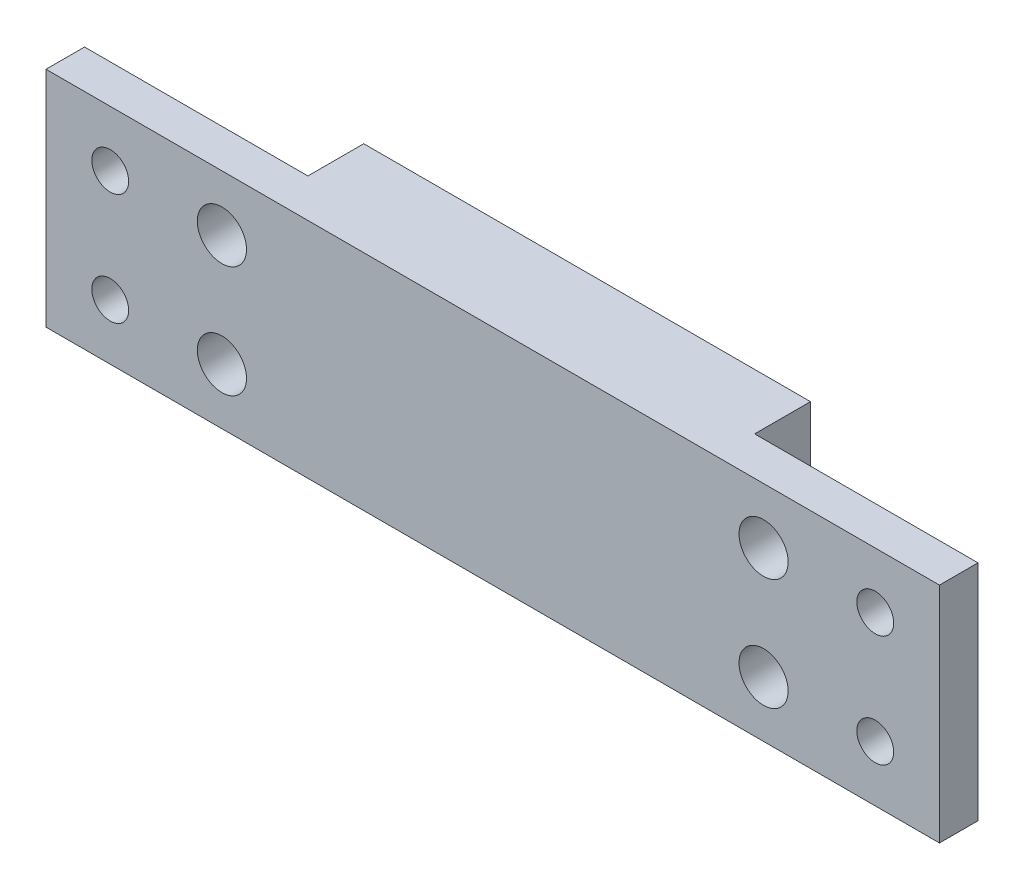
SolidWorks part; units mm, degrees
ref_plane "前视基准面" through (0, 0, 0) normal (0, 0, 1) x (1, 0, 0)
ref_plane "上视基准面" through (0, 0, 0) normal (0, 1, 0) x (1, 0, 0)
ref_plane "右视基准面" through (0, 0, 0) normal (1, 0, 0) x (0, 0, -1)
other "Configuration Table"
sketch "草图1" plane through (0, 0, 0) normal (0, 0, 1) x (1, 0, 0)
  line L1 (0, 0) -> (60, 0)
  line L2 (0, 0) -> (0, 20)
  line L3 (0, 20) -> (60, 20)
  line L4 (60, 0) -> (60, 20)
  dimension "D1" = 60
  dimension "D2" = 20
extrude "凸台-拉伸1" add sketch "草图1" along normal blind 3.45
sketch "草图2" plane through (0, 0, 0) normal (0, 0, -1) x (-1, 0, 0)
  line L0 (0, 0) -> (-60, 0) construction
  line L1 (-50, 0) -> (-10, 0)
  line L2 (-50, 0) -> (-50, 20)
  line L3 (-50, 20) -> (-10, 20)
  line L4 (-10, 0) -> (-10, 20)
  line L5 (-60, 20) -> (0, 20) construction
  line L6 (-30, 20) -> (-30, -10.5906) construction
  point P10 (-30, 20)
  point P11 (-30, 20)
  dimension "D1" = 40
extrude "凸台-拉伸2" add sketch "草图2" along normal blind 5
sketch "草图4" plane through (0, 0, 0) normal (0, 0, -1) x (-1, 0, 0)
  line L0 (0, 20) -> (0, 0) construction
  line L1 (-70, 0) -> (10, 0)
  line L2 (-70, 0) -> (-70, 20)
  line L3 (-70, 20) -> (10, 20)
  line L4 (10, 0) -> (10, 20)
  line L5 (-60, 0) -> (-60, 20) construction
  dimension "D1" = 10
  dimension "D2" = 10
extrude "凸台-拉伸3" add sketch "草图4" against normal blind 3.45
sketch "草图7" plane through (0, 0, 3.45) normal (0, 0, 1) x (1, 0, 0)
  circle A0 centre (5.75, 15.0015) radius 2.2
  circle A1 centre (54.25, 15) radius 2.2
  circle A2 centre (54.25, 5) radius 2.2
  circle A3 centre (5.75, 5) radius 2.2
  circle A4 centre (-4.25, 15.0004) radius 1.65
  circle A5 centre (-4.25, 5) radius 1.65
  circle A6 centre (64.25, 5) radius 1.65
  circle A7 centre (64.25, 15) radius 1.65
  point P16 (0, 0)
  point P17 (5.75, 15.0004)
  point P18 (54.25, 15)
  dimension "D1" = 3.3
  dimension "D2" = 3.3
  dimension "D3" = 3.3
  dimension "D4" = 3.3
  dimension "D5" = 10
  dimension "D6" = 10
extrude "切除-拉伸1" cut sketch "草图7" against normal blind 3.45
